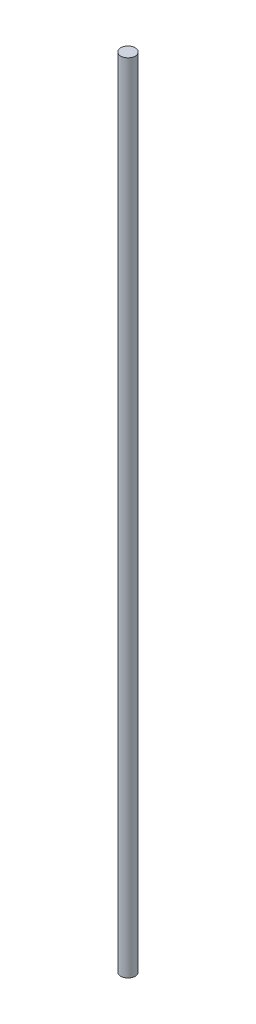
SolidWorks part; units mm, degrees
ref_plane "Front Plane" through (0, 0, 0) normal (0, 0, 1) x (1, 0, 0)
ref_plane "Top Plane" through (0, 0, 0) normal (0, 1, 0) x (1, 0, 0)
ref_plane "Right Plane" through (0, 0, 0) normal (1, 0, 0) x (0, 0, -1)
sketch "Sketch1" plane through (0, 0, 0) normal (0, 1, 0) x (1, 0, 0)
  circle A0 centre (0, 0) radius 2.5
  dimension "D1" = 5
extrude "Boss-Extrude1" add sketch "Sketch1" along normal blind 275
